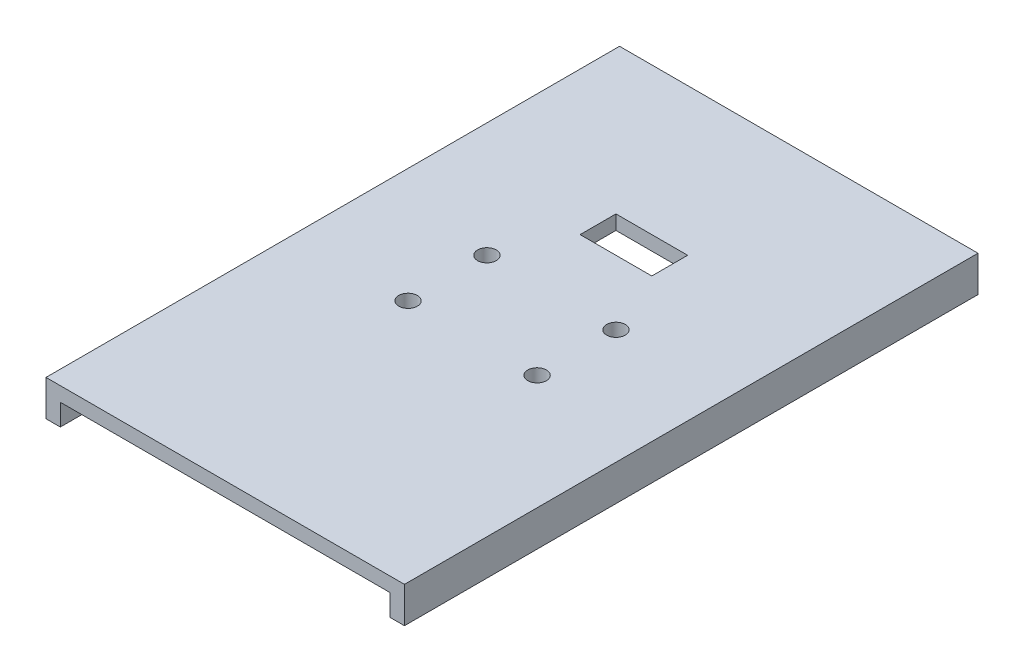
SolidWorks part; units mm, degrees
ref_plane "Front Plane" through (0, 0, 0) normal (0, 0, 1) x (1, 0, 0)
ref_plane "Top Plane" through (0, 0, 0) normal (0, 1, 0) x (1, 0, 0)
ref_plane "Right Plane" through (0, 0, 0) normal (1, 0, 0) x (0, 0, -1)
sketch "Sketch1" plane through (0, 0, 0) normal (0, 1, 0) x (1, 0, 0)
  line L1 (0, 0) -> (40, 0)
  line L2 (0, 0) -> (0, 80)
  line L3 (0, 80) -> (40, 80)
  line L4 (40, 0) -> (40, 80)
  dimension "D1" = 40
  dimension "D2" = 80
extrude "Boss-Extrude1" add sketch "Sketch1" along normal blind 2
sketch "Sketch2" plane through (0, 0, 0) normal (0, 0, 1) x (1, 0, 0)
  line L0 (0, 2) -> (-5, 2)
  line L1 (-5, 2) -> (-5, -3)
  line L2 (-5, -3) -> (-3, -3)
  line L3 (-3, -3) -> (-3, 0)
  line L4 (-3, 0) -> (0, 0)
  line L5 (0, 0) -> (0, 2)
  line L6 (20, 0) -> (20, 12.7492) construction
  line L8 (0, 0) -> (40, 0) construction
  line L9 (43, 0) -> (40, 0)
  line L10 (43, -3) -> (43, 0)
  line L11 (45, -3) -> (43, -3)
  line L12 (45, 2) -> (45, -3)
  line L13 (40, 2) -> (45, 2)
  line L14 (40, 0) -> (40, 2)
  point P11 (20, 0)
  dimension "D1" = 2
  dimension "D2" = 5
  dimension "D3" = 5
extrude "Boss-Extrude2" add sketch "Sketch2" against normal up to vertex (80 mm away)
sketch "Sketch3" plane through (0, 2, 0) normal (0, 1, 0) x (1, 0, 0)
  line L0 (20, 0) -> (20, 81.8773) construction
  line L1 (-5, 80) -> (-5, 0) construction
  line L3 (-5, 0) -> (45, 0) construction
  line L4 (-5, 40) -> (58.6355, 40) construction
  line L6 (15, 59.5) -> (25, 59.5)
  line L7 (15, 59.5) -> (15, 54.5)
  line L8 (15, 54.5) -> (25, 54.5)
  line L9 (25, 59.5) -> (25, 54.5)
  circle A0 centre (11, 45.5) radius 1.3
  circle A3 centre (11, 34.5) radius 1.3
  circle A4 centre (29, 45.5) radius 1.3
  circle A5 centre (29, 34.5) radius 1.3
  point P3 (20, 40.9387)
  point P5 (20, 0)
  point P9 (-5, 40)
  point P19 (25, 57)
  point P24 (20, 54.5)
  dimension "D1" = 2.6
  dimension "D4" = 9
  dimension "D2" = 5.5
  dimension "D3" = 11
  dimension "D5" = 5
  dimension "D6" = 10
  dimension "D7" = 17
extrude "Cut-Extrude1" cut sketch "Sketch3" against normal blind 2
